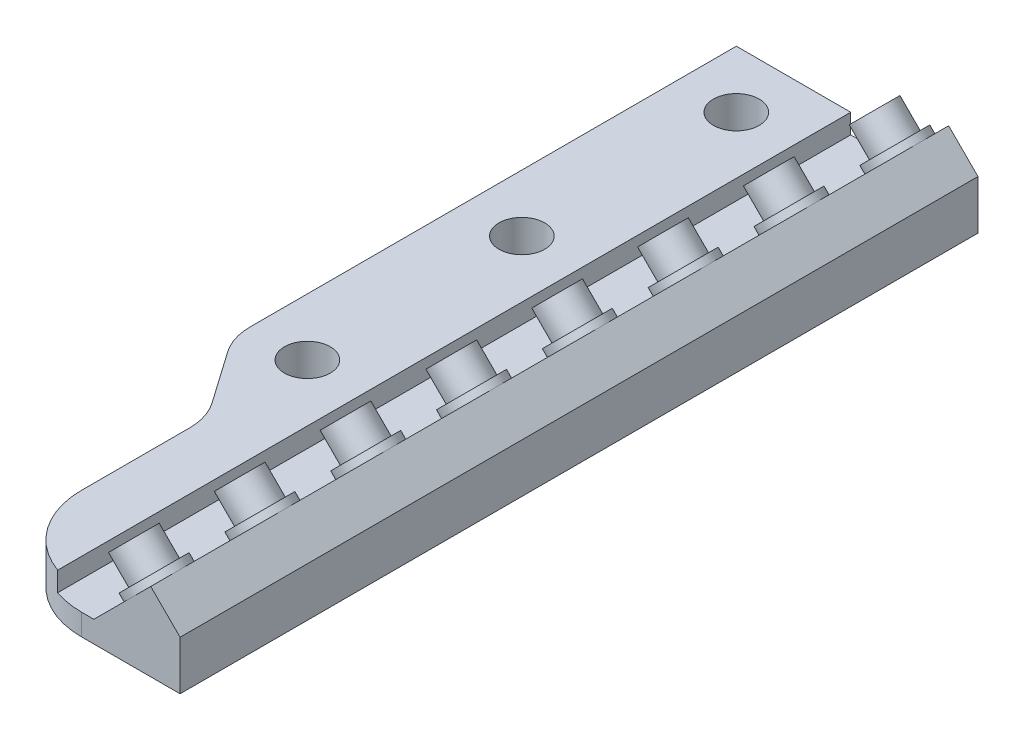
SolidWorks part; units mm, degrees
material "光敏树脂"
ref_plane "前视基准面" through (0, 0, 0) normal (0, 0, 1) x (1, 0, 0)
ref_plane "上视基准面" through (0, 0, 0) normal (0, 1, 0) x (1, 0, 0)
ref_plane "右视基准面" through (0, 0, 0) normal (1, 0, 0) x (0, 0, -1)
sketch "草图1" plane through (0, 0, 0) normal (0, 0, 1) x (1, 0, 0)
  line L0 (16.9, 0) -> (16.9, 3.4266)
  line L1 (16.9, 3.4266) -> (14.849, 5.4777)
  line L2 (14.849, 5.4777) -> (14.4954, 5.1241)
  line L3 (14.4954, 5.1241) -> (12.3741, 7.2454) construction
  line L4 (12.3741, 7.2454) -> (12.7277, 7.599) construction
  line L5 (12.7277, 7.599) -> (10.6633, 9.6633) construction
  line L6 (10.6633, 9.6633) -> (8, 7) construction
  line L7 (8, 7) -> (0, 7) construction
  line L8 (0, 7) -> (0, 0) construction
  line L9 (0, 0) -> (16.9, 0)
  line L10 (12.3741, 3.0028) -> (10.2528, 5.1241) construction
  line L11 (10.2528, 5.1241) -> (8, 2.8713) construction
  line L12 (8, 2.8713) -> (8, 1.5)
  line L13 (8, 1.5) -> (10.8713, 1.5)
  line L14 (10.8713, 1.5) -> (12.3741, 3.0028)
  line L15 (8, 2.8713) -> (0, 2.8713)
  line L16 (14.4954, 5.1241) -> (12.3741, 3.0028)
  line L17 (0, 2.8713) -> (0, 0)
  dimension "D1" = 3
  dimension "D2" = 45
  dimension "D3" = 16.9
  dimension "D4" = 3
  dimension "D5" = 1.5
  dimension "D6" = 8
  dimension "D7" = 7
  dimension "D8" = 3.4266
  dimension "D9" = 2.9006
  dimension "D10" = 0.5
extrude "凸台-拉伸1" add sketch "草图1" along normal blind 63.5
sketch "草图2" plane through (4.6857, -4.6857, 0) normal (-0.7071, 0.7071, 0) x (0, 0, 1)
  line L0 (63.5, 14.3731) -> (0, 14.3731) construction
  line L1 (0, 14.3731) -> (0, 8.7478) construction
  line L2 (38, -4.3204) -> (38, 21.4734) construction
  line L3 (0, 7.6872) -> (0, 2.0303) construction
  circle A0 centre (2, 12.3731) radius 1.45
  circle A1 centre (2, 12.3731) radius 3.5 construction
  circle A2 centre (9.4, 12.3731) radius 3.5 construction
  circle A3 centre (16.8, 12.3731) radius 3.5 construction
  circle A4 centre (24.2, 12.3731) radius 3.5 construction
  circle A5 centre (31.6, 12.3731) radius 3.5 construction
  circle A6 centre (39, 12.3731) radius 3.5 construction
  circle A7 centre (46.4, 12.3731) radius 3.5 construction
  circle A8 centre (53.8, 12.3731) radius 3.5 construction
  circle A9 centre (61.2, 12.3731) radius 3.5 construction
  circle A11 centre (5.8441, 36.9744) radius 21.25 construction
  circle A12 centre (2, 36.9744) radius 21.25 construction
  circle A13 centre (61.2, 12.3731) radius 2 construction
  circle A14 centre (31.6, 12.3731) radius 2 construction
  dimension "D1" = 2.9
  dimension "D3" = 2
  dimension "D4" = 7
  dimension "D6" = 4
  dimension "D7" = 42.5
  dimension "D8" = 42.5
  dimension "D10" = 38
  dimension "D11" = 4
  dimension "D2" = 2
  dimension "D9" = 7.4
  dimension "D5" = 9
extrude "凸台-拉伸2" add sketch "草图2" along normal blind 2.5
sketch "草图3" plane through (4.6857, -4.6857, 0) normal (-0.7071, 0.7071, 0) x (0, 0, 1)
  circle A0 centre (2, 12.3731) radius 2
  dimension "D1" = 4
extrude "凸台-拉伸3" add sketch "草图3" along normal blind 0.5
pattern_linear "阵列(线性)1" count 9 spacing 7.4 along (0, 0, 1) of "凸台-拉伸2", "凸台-拉伸3"
sketch "草图4" plane through (0, 2.8713, 0) normal (0, 1, 0) x (1, 0, 0)
  line L0 (0, -63.5) -> (0, 0) construction
  line L1 (8, 0) -> (0, 0) construction
  circle A0 centre (4, -4) radius 1.6
  dimension "D1" = 3.2
  dimension "D2" = 4
  dimension "D3" = 4
extrude "切除-拉伸1" cut sketch "草图4" against normal blind 10.5
pattern_linear "阵列(线性)2" count 3 spacing 15 along (0, 0, 1) of "切除-拉伸1"
sketch "草图6" plane through (0, 2.8713, 0) normal (0, 1, 0) x (1, 0, 0)
  line L1 (4, -40.9738) -> (0.7234, -36.2943)
  line L2 (4, -34) -> (4, -40.9738) construction
  line L3 (0, -34) -> (-4.8482, -34)
  line L4 (-4.8482, -34) -> (-4.8482, -69.5683)
  line L5 (-4.8482, -69.5683) -> (19.4471, -69.5683)
  line L6 (19.4471, -69.5683) -> (19.4471, -55.8)
  line L7 (4, -40.9738) -> (4, -55.8)
  line L8 (4, -55.8) -> (19.4471, -55.8)
  line L9 (0, -63.5) -> (0, 0) construction
  arc A0 (0, -34) -> (0.7234, -36.2943) centre (4, -34) ccw
  circle A2 centre (4, -34) radius 1.6 construction
  dimension "D1" = 145
  dimension "D2" = 8
  dimension "D3" = 21.8
extrude "切除-拉伸2" cut sketch "草图6" against normal mid plane 10
fillet "圆角1" radius 6 1 edges at (4, 1.4357, 55.8)
fillet "圆角2" radius 4 1 edges at (4, 1.4357, 40.9738)
